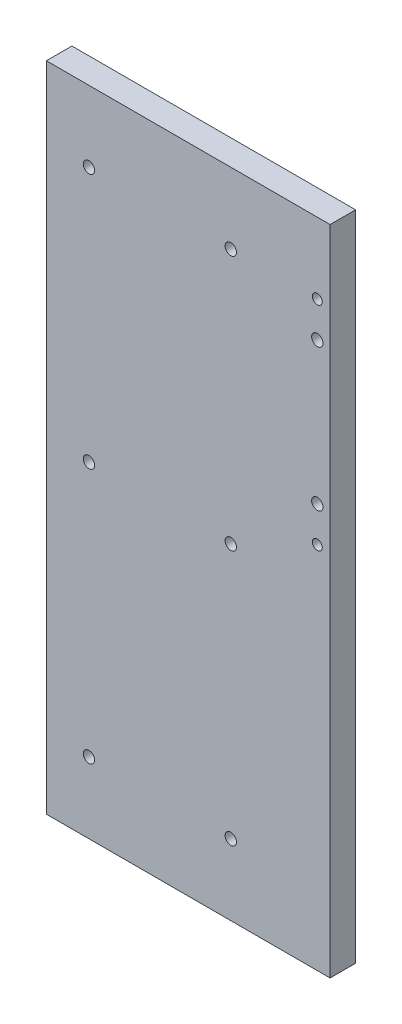
SolidWorks part; units mm, degrees
ref_plane "Front Plane" through (0, 0, 0) normal (0, 0, 1) x (1, 0, 0)
ref_plane "Top Plane" through (0, 0, 0) normal (0, 1, 0) x (1, 0, 0)
ref_plane "Right Plane" through (0, 0, 0) normal (1, 0, 0) x (0, 0, -1)
sketch "Sketch1" plane through (0, 0, 0) normal (0, 0, 1) x (1, 0, 0)
  line L1 (-100, 230) -> (100, 230)
  line L2 (-100, 230) -> (-100, -230)
  line L3 (-100, -230) -> (100, -230)
  line L4 (100, 230) -> (100, -230)
  line L5 (-100, 230) -> (100, -230) construction
  line L6 (-100, -230) -> (100, 230) construction
  point P0 (0, 0)
  dimension "D1" = 460
  dimension "D2" = 200
extrude "Boss-Extrude1" add sketch "Sketch1" along normal blind 18
hole_wizard "Otwory ustalające Ø8.0mm1" positions "Szkic2" profile "Szkic1" hole size "Ø8.0" standard "ISO" end condition through all
sketch "Szkic2" plane through (0, 0, 18) normal (0, 0, 1) x (1, 0, 0)
  point P0 (30, -180)
  point P3 (-70, -180)
  point P6 (-70, 0)
  point P9 (30, 0)
  point P12 (30, 180)
  point P15 (-70, 180)
sketch "Szkic1" plane through (30, -180, 18) normal (1, 0, 0) x (0, -1, 0)
  line L0 (0, 0) -> (0, 18)
  line L1 (0, 18) -> (4, 18)
  line L2 (4, 18) -> (4, 0)
  line L5 (4, 0) -> (0, 0)
  line L11 (0, -6.35) -> (0, 107.95) construction
  dimension "Średnica otworu na wylot" = 8
  dimension "Głębokość otworu na wylot" = 18
hole_wizard "Otwór Ø7.0 (7)1" positions "Szkic4" profile "Szkic3" hole size "Ø7.0" standard "ISO" end condition through all
sketch "Szkic4" plane through (0, 0, 18) normal (0, 0, 1) x (1, 0, 0)
  point P0 (91, 30)
  point P3 (91, 180)
sketch "Szkic3" plane through (91, 30, 18) normal (1, 0, 0) x (0, -1, 0)
  line L0 (0, 0) -> (0, 18)
  line L1 (0, 18) -> (3.5, 18)
  line L2 (3.5, 18) -> (3.5, 0)
  line L5 (3.5, 0) -> (0, 0)
  line L11 (0, -6.35) -> (0, 107.95) construction
  dimension "Średnica otworu na wylot" = 7
  dimension "Głębokość otworu na wylot" = 18
hole_wizard "Otwór Ø5.0 (5)1" positions "Szkic6" profile "Szkic5" hole size "Ø5.0" standard "ISO"
sketch "Szkic6" plane through (0, -230, 0) normal (0, -1, 0) x (-1, 0, 0)
  line L0 (100, 0) -> (-100, 0) construction
  line L1 (-100, -18) -> (-100, 0) construction
  line L2 (100, -18) -> (100, 0) construction
  point P0 (-50, -9)
  point P2 (50, -9)
  dimension "D1" = 9
  dimension "D2" = 9
  dimension "D3" = 50
  dimension "D4" = 50
sketch "Szkic5" plane through (50, -230, 9) normal (1, 0, 0) x (0, 0, -1)
  line L0 (0, 0) -> (0, 46.5022)
  line L1 (0, 46.5022) -> (2.5, 45)
  line L2 (2.5, 45) -> (2.5, 0)
  line L5 (2.5, 0) -> (0, 0)
  line L10 (0, 46.5022) -> (-2.5, 45) construction
  line L11 (0, -6.35) -> (0, 107.95) construction
  dimension "Średnica otworu" = 5
  dimension "Głębokość otworu" = 45
  dimension "Kąt wiertła" = 118
hole_wizard "Otwór Ø8.0 (8)1" positions "Szkic8" profile "Szkic7" hole size "Ø8.0" standard "ISO"
sketch "Szkic8" plane through (0, 0, 18) normal (0, 0, 1) x (1, 0, 0)
  point P2 (91, 55)
  point P8 (91, 155)
sketch "Szkic7" plane through (91, 55, 18) normal (1, 0, 0) x (0, -1, 0)
  line L0 (0, 0) -> (0, 17.4034)
  line L1 (0, 17.4034) -> (4, 15)
  line L2 (4, 15) -> (4, 0)
  line L5 (4, 0) -> (0, 0)
  line L10 (0, 17.4034) -> (-4, 15) construction
  line L11 (0, -6.35) -> (0, 107.95) construction
  dimension "Średnica otworu" = 8
  dimension "Głębokość otworu" = 15
  dimension "Kąt wiertła" = 118
hole_wizard "Otwór Ø8.0 (8)2" positions "Szkic10" profile "Szkic9" hole size "Ø8.0" standard "ISO"
sketch "Szkic10" plane through (0, -230, 0) normal (0, -1, 0) x (-1, 0, 0)
  line L0 (100, 0) -> (-100, 0) construction
  line L1 (-100, -18) -> (-100, 0) construction
  point P0 (0, -9)
  dimension "D1" = 9
  dimension "D2" = 100
sketch "Szkic9" plane through (0, -230, 9) normal (1, 0, 0) x (0, 0, -1)
  line L0 (0, 0) -> (0, 24.4034)
  line L1 (0, 24.4034) -> (4, 22)
  line L2 (4, 22) -> (4, 0)
  line L5 (4, 0) -> (0, 0)
  line L10 (0, 24.4034) -> (-4, 22) construction
  line L11 (0, -6.35) -> (0, 107.95) construction
  dimension "Średnica otworu" = 8
  dimension "Głębokość otworu" = 22
  dimension "Kąt wiertła" = 118
